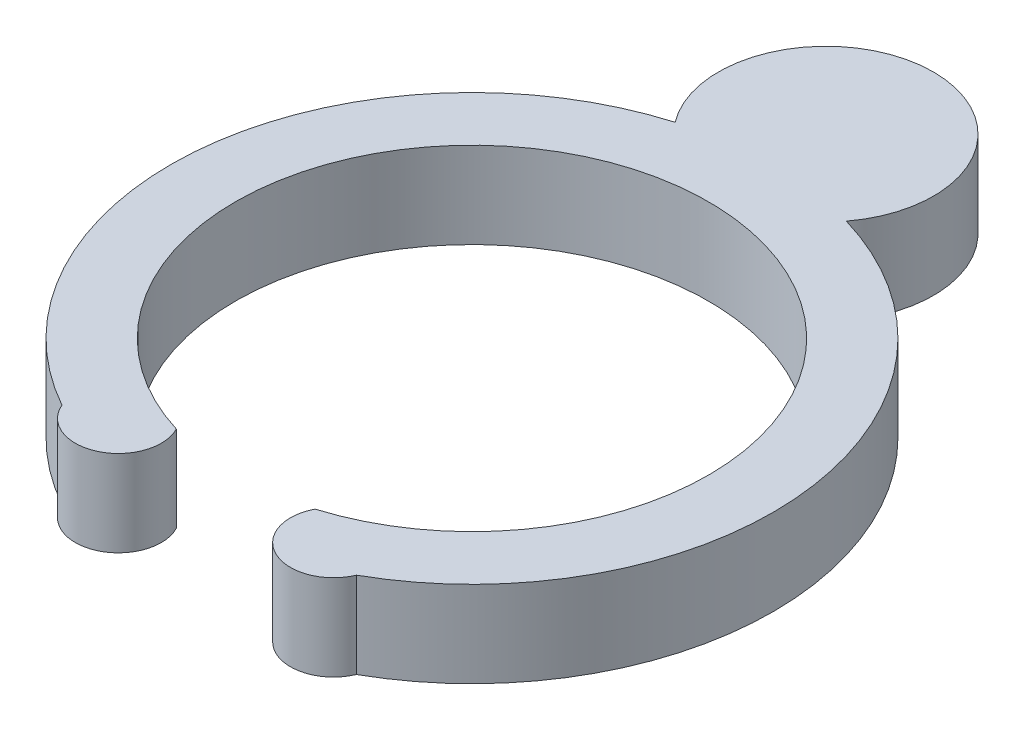
SolidWorks part; units mm, degrees
material "PBT General Purpose"
ref_plane "Front Plane" through (0, 0, 0) normal (0, 0, 1) x (1, 0, 0)
ref_plane "Top Plane" through (0, 0, 0) normal (0, 1, 0) x (1, 0, 0)
ref_plane "Right Plane" through (0, 0, 0) normal (1, 0, 0) x (0, 0, -1)
sketch "Sketch1" plane through (0, 0, 0) normal (0, 1, 0) x (1, 0, 0)
  circle A0 centre (0, 0) radius 7
  dimension "D1" = 14
extrude "Boss-Extrude1" add sketch "Sketch1" along normal blind 2
sketch "Sketch2" plane through (0, 2, 0) normal (0, 1, 0) x (1, 0, 0)
  circle A0 centre (0, 0) radius 5.5
  dimension "D1" = 11
extrude "Cut-Extrude1" cut sketch "Sketch2" against normal blind 2
sketch "Sketch3" plane through (0, 0, 0) normal (0, -1, 0) x (1, 0, 0)
  line L0 (0, -7) -> (0, -7.5847) construction
  line L1 (0, -7.5847) -> (0, -7.957) construction
  line L2 (0, -7) -> (0, -8.226) construction
  circle A0 centre (0, 0) radius 7 construction
  circle A1 centre (0, -8.226) radius 2.5
  dimension "D1" = 5
extrude "Boss-Extrude4" add sketch "Sketch3" against normal blind 2
sketch "Sketch4" plane through (0, 2, 0) normal (0, 1, 0) x (1, 0, 0)
  line L1 (-2.5, -4.3295) -> (2.5, -4.3295)
  line L2 (-2.5, -4.3295) -> (-2.5, -9.6705)
  line L3 (-2.5, -9.6705) -> (2.5, -9.6705)
  line L4 (2.5, -4.3295) -> (2.5, -9.6705)
  line L5 (-2.5, -4.3295) -> (2.5, -9.6705) construction
  line L6 (-2.5, -9.6705) -> (2.5, -4.3295) construction
  arc A0 (-1.989, 6.7115) -> (1.989, 6.7115) centre (0, 0) ccw construction
  point P0 (0, -7)
  dimension "D1" = 5
extrude "Cut-Extrude4" cut sketch "Sketch4" against normal blind 2
sketch "Sketch6" plane through (0, 2, 0) normal (0, 1, 0) x (1, 0, 0)
  line L0 (2.5, -6.5383) -> (2.5, -4.899) construction
  circle A0 centre (2.5, -5.7187) radius 1
  dimension "D1" = 2
extrude "Boss-Extrude6" add sketch "Sketch6" against normal blind 2
ref_plane "Plane1" through (-2.5, 2, 6.5383) normal (0, 0, 1) x (1, 0, 0)
sketch "Sketch8" plane through (0, 2, 0) normal (0, 1, 0) x (1, 0, 0)
  line L0 (-2.5, -4.899) -> (-2.5, -6.5383) construction
  circle A0 centre (-2.5, -5.7187) radius 1
  dimension "D1" = 2
extrude "Boss-Extrude7" add sketch "Sketch8" against normal blind 2
sketch "Sketch9" plane through (0, 2, 0) normal (0, 1, 0) x (1, 0, 0)
  circle A0 centre (0, 0) radius 5.5
extrude "Cut-Extrude5" cut sketch "Sketch9" against normal blind 2
